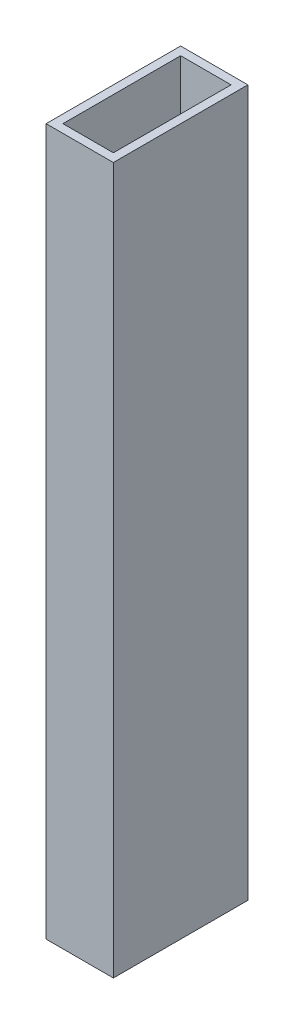
SolidWorks part; units mm, degrees
ref_plane "Front Plane" through (0, 0, 0) normal (0, 0, 1) x (1, 0, 0)
ref_plane "Top Plane" through (0, 0, 0) normal (0, 1, 0) x (1, 0, 0)
ref_plane "Right Plane" through (0, 0, 0) normal (1, 0, 0) x (0, 0, -1)
sketch "Sketch1" plane through (0, 0, 0) normal (0, 1, 0) x (1, 0, 0)
  line L0 (-9.525, 22.225) -> (9.525, 22.225)
  line L1 (-12.7, -25.4) -> (12.7, -25.4)
  line L2 (-12.7, -25.4) -> (-12.7, 25.4)
  line L3 (-12.7, 25.4) -> (12.7, 25.4)
  line L4 (12.7, -25.4) -> (12.7, 25.4)
  line L5 (-12.7, -25.4) -> (12.7, 25.4) construction
  line L6 (-12.7, 25.4) -> (12.7, -25.4) construction
  line L7 (9.525, -22.225) -> (9.525, 22.225)
  line L8 (-9.525, -22.225) -> (9.525, -22.225)
  line L9 (-9.525, -22.225) -> (-9.525, 22.225)
  point P0 (0, 0)
  dimension "D1" = 25.4
  dimension "D2" = 50.8
  dimension "D3" = 3.175
extrude "Boss-Extrude1" add sketch "Sketch1" along normal blind 266.7
